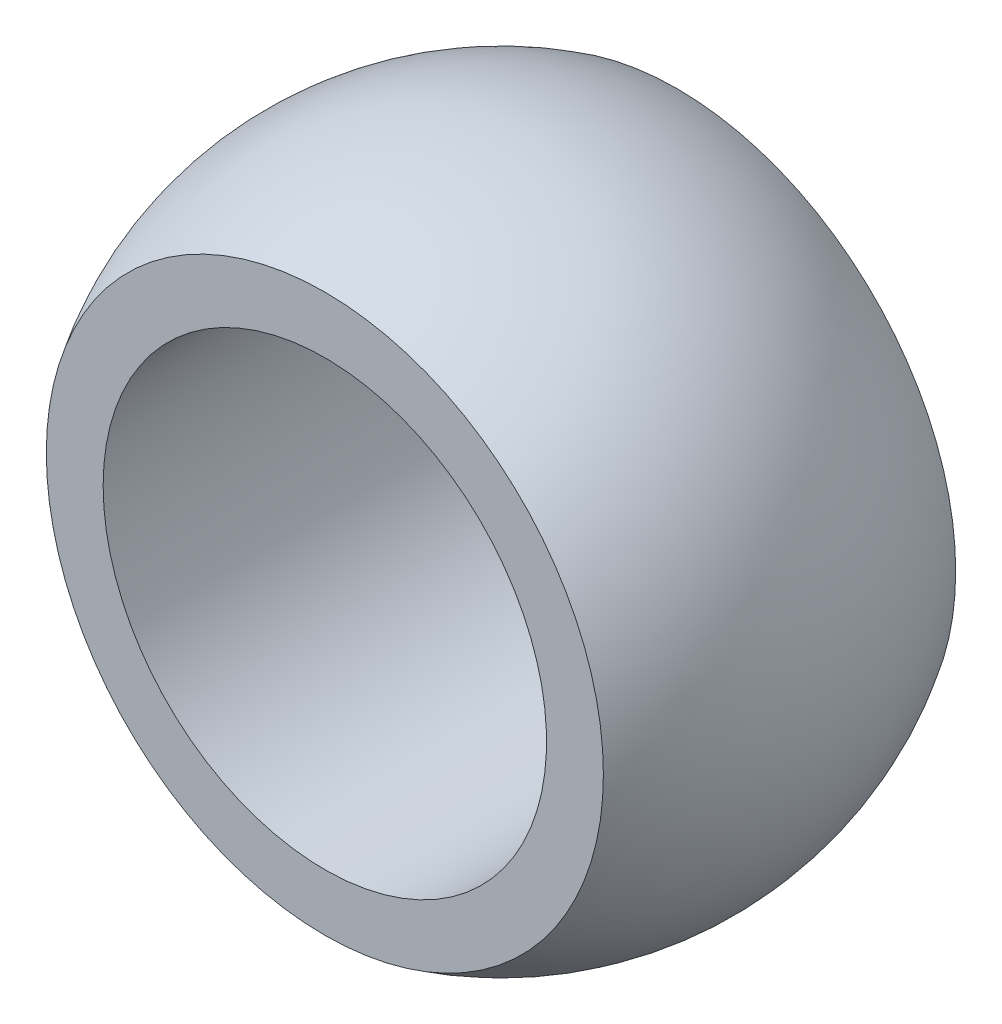
SolidWorks part; units mm, degrees
material "Литая легированная сталь"
ref_plane "Спереди" through (0, 0, 0) normal (0, 0, 1) x (1, 0, 0)
ref_plane "Сверху" through (0, 0, 0) normal (0, 1, 0) x (1, 0, 0)
ref_plane "Справа" through (0, 0, 0) normal (1, 0, 0) x (0, 0, -1)
sketch "Эскиз1" plane through (0, 0, 0) normal (0, 0, 1) x (1, 0, 0)
  line L0 (0, 0) -> (0, 29) construction
  line L1 (0, 29) -> (0, -29)
  arc A0 (0, -29) -> (0, 29) centre (0, 0) ccw
  dimension "D1" = 58
revolve "Повернуть1" add sketch "Эскиз1" angle 360 about L0
sketch "Эскиз2" plane through (0, 0, 0) normal (0, 0, 1) x (1, 0, 0)
  circle A1 centre (0, 0) radius 29 construction
  circle A3 centre (0, 0) radius 29
extrude "Вырез-Вытянуть1" cut sketch "Эскиз2" against normal through all from offset 15.5 offset against normal yes
mirror "Зеркальное отражение1" about plane through (0, 0, 0) normal (0, 0, 1) of "Вырез-Вытянуть1"
sketch "Эскиз3" plane through (0, 0, -15.5) normal (0, 0, -1) x (-1, 0, 0)
  circle A2 centre (0, 0) radius 19.5102
  circle A3 centre (0, 0) radius 19.5102
  dimension "D1" = 5
extrude "Вырез-Вытянуть2" cut sketch "Эскиз3" against normal through all
